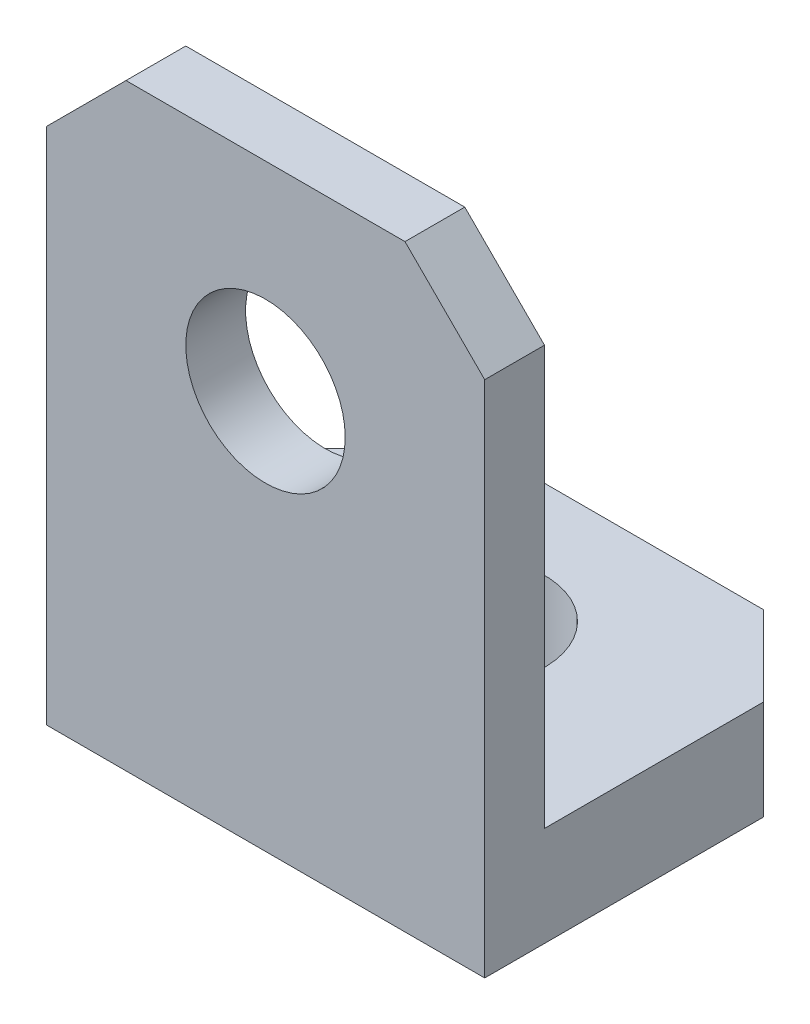
SolidWorks part; units mm, degrees
ref_plane "前视基准面" through (0, 0, 0) normal (0, 0, 1) x (1, 0, 0)
ref_plane "上视基准面" through (0, 0, 0) normal (0, 1, 0) x (1, 0, 0)
ref_plane "右视基准面" through (0, 0, 0) normal (1, 0, 0) x (0, 0, -1)
sketch "草图1" plane through (0, 0, 0) normal (0, 1, 0) x (1, 0, 0)
  line L0 (-0.4672, -11.9768) -> (-0.4672, -1.9768) construction
  line L1 (-11.4672, 6.0232) -> (10.5328, 6.0232)
  line L2 (-11.4672, 6.0232) -> (-11.4672, -11.9768)
  line L3 (-11.4672, -11.9768) -> (10.5328, -11.9768)
  line L4 (10.5328, 6.0232) -> (10.5328, -11.9768)
  circle A0 centre (-0.4672, -1.9768) radius 4
  dimension "D3" = 8
  dimension "D1" = 22
  dimension "D2" = 18
  dimension "D4" = 10
extrude "凸台-拉伸1" add sketch "草图1" along normal blind 5
sketch "草图2" plane through (0, 0, 11.9768) normal (0, 0, 1) x (1, 0, 0)
  line L0 (-0.4672, 5) -> (-0.4672, 20) construction
  line L1 (-11.4672, 5) -> (10.5328, 5)
  line L2 (-11.4672, 5) -> (-11.4672, 30)
  line L3 (-11.4672, 30) -> (10.5328, 30)
  line L4 (10.5328, 5) -> (10.5328, 30)
  circle A0 centre (-0.4672, 20) radius 4
  dimension "D4" = 8
  dimension "D1" = 25
  dimension "D2" = 22
  dimension "D3" = 15
extrude "凸台-拉伸2" add sketch "草图2" against normal blind 3
chamfer "倒角1" distance 4 angle 45 4 edges at (10.5328, 2.5, -6.0232) (-11.4672, 2.5, -6.0232) (10.5328, 30, 10.4768) (-11.4672, 30, 10.4768)
